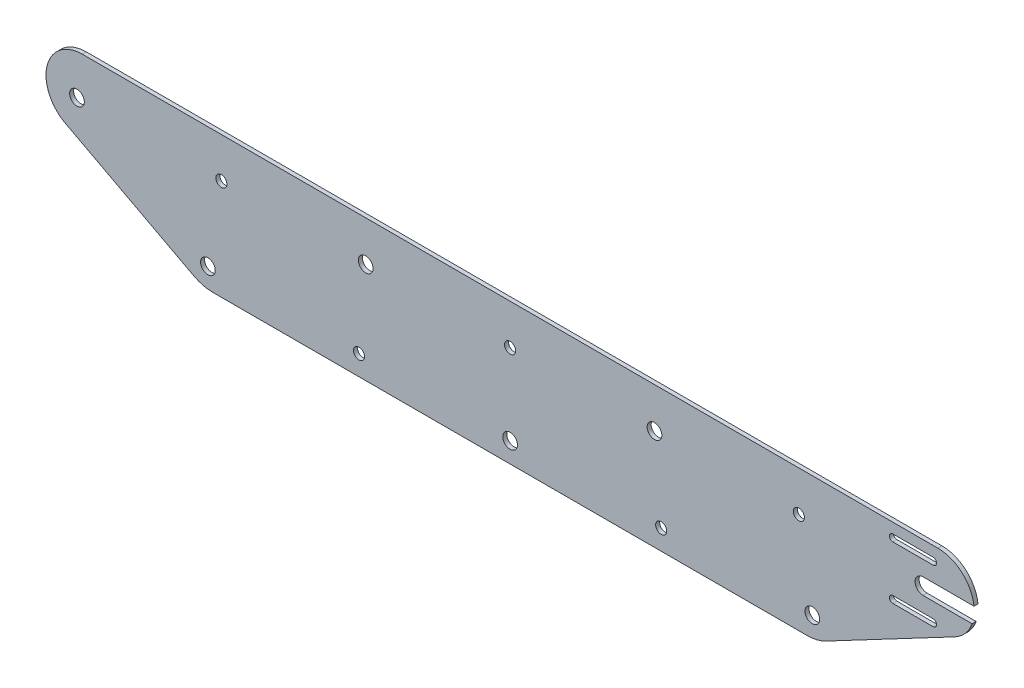
SolidWorks part; units mm, degrees
ref_plane "Plan de face" through (0, 0, 0) normal (0, 0, 1) x (1, 0, 0)
ref_plane "Plan de dessus" through (0, 0, 0) normal (0, 1, 0) x (1, 0, 0)
ref_plane "Plan de droite" through (0, 0, 0) normal (1, 0, 0) x (0, 0, -1)
sketch "Esquisse1" plane through (0, 0, 0) normal (0, 0, 1) x (1, 0, 0)
  line L0 (0, 0) -> (0, 122.747) construction
  line L1 (-215, -20) -> (215, -20) construction
  line L2 (-215, -20) -> (-215, 20) construction
  line L3 (-215, 20) -> (215, 20) construction
  line L4 (215, -20) -> (215, 20) construction
  line L5 (-215, -20) -> (215, 20) construction
  line L6 (-215, 20) -> (215, -20) construction
  line L7 (-1220, 0) -> (-150, 0) construction
  line L8 (-284.959, 40) -> (-150, 40)
  line L9 (150, 40) -> (284.959, 40)
  line L10 (150, 0) -> (150, -20) construction
  line L11 (150, -20) -> (-150, -20) construction
  line L12 (-150, 0) -> (-150, -20) construction
  line L13 (150, 0) -> (-150, -20) construction
  line L14 (150, -20) -> (-150, 0) construction
  line L15 (-284.959, 40) -> (-152.4795, -30)
  line L16 (-152.4795, -30) -> (152.4795, -30)
  line L17 (284.959, 40) -> (152.4795, -30)
  line L18 (-215, 20) -> (-71.6667, 20) construction
  line L19 (-71.6667, 20) -> (71.6667, 20) construction
  line L20 (71.6667, 20) -> (215, 20) construction
  line L21 (150, 0) -> (193.5165, 0) construction
  line L22 (150, 95) -> (-150, 95) construction
  line L23 (150, 95) -> (150, 40) construction
  line L24 (-150, 40) -> (150, 40)
  line L25 (-150, 95) -> (-150, 40) construction
  line L26 (150, 95) -> (-150, 0) construction
  line L27 (150, 0) -> (-150, 95) construction
  circle A0 centre (-215, 20) radius 3.65
  circle A1 centre (-150, -20) radius 3.65
  circle A2 centre (150, -20) radius 3.65
  circle A3 centre (215, 20) radius 3.65
  circle A4 centre (0, -20) radius 3.65
  circle A5 centre (-71.6667, 20) radius 3.65
  circle A6 centre (71.6667, 20) radius 3.65
  circle A7 centre (0, 78.03) radius 3.65 construction
  point P0 (0, 0)
  point P8 (0, -10)
  point P20 (0, 47.5)
  point P21 (0, -30)
  point P31 (0, 47.5)
  dimension "D8" = 7.3
  dimension "D10" = 58.03
  dimension "D1" = 430
  dimension "D2" = 40
  dimension "D3" = 300
  dimension "D4" = 20
  dimension "D5" = 15
  dimension "D6" = 10
  dimension "D7" = 10
  dimension "D9" = 55
extrude "Boss.-Extru.1" add sketch "Esquisse1" along normal blind 2
fillet "Congé1" radius 18 2 edges at (-284.959, 40, 1) (284.959, 40, 1)
fillet "Congé2" radius 20 2 edges at (-152.4795, -30, 1) (152.4795, -30, 1)
hole_wizard "Dégagement M31" positions "Esquisse3" profile "Esquisse2" hole size "M3" standard "Ansi Metric" end condition through all
sketch "Esquisse3" plane through (0, 0, 0) normal (0, 0, -1) x (-1, 0, 0)
  line L0 (-215, 12.5) -> (-215, 20)
  line L1 (-200, 6.7712) -> (-200, 33.2288)
  circle A0 centre (-215, 20) radius 7.5
  circle A1 centre (-215, 20) radius 20
  point P0 (-200, 33.2288)
  point P29 (-200, 6.7712)
  dimension "D2" = 15
  dimension "D3" = 40
  dimension "D1" = 15
sketch "Esquisse2" plane through (200, 33.2288, 0) normal (1, 0, 0) x (0, 1, 0)
  line L0 (0, 0) -> (0, 2)
  line L1 (0, 2) -> (1.7, 2)
  line L2 (1.7, 2) -> (1.7, 0)
  line L5 (1.7, 0) -> (0, 0)
  line L11 (0, -6.35) -> (0, 107.95) construction
  dimension "Diamètre du perçage jusqu'au prochain" = 3.4
  dimension "Profondeur du perçage jusqu'au prochain" = 2
sketch "Esquisse4" plane through (0, 0, 0) normal (0, 0, -1) x (-1, 0, 0)
  line L0 (-215, 24) -> (-230.2521, 24)
  line L1 (-215, 24) -> (-205, 24)
  line L2 (-215, 16) -> (-205, 16)
  line L3 (-215, 16) -> (-229.3341, 16)
  line L4 (-147.5205, -30) -> (147.5205, -30)
  line L5 (156.8641, -27.6833) -> (220.7728, 6.0851)
  line L6 (212.3636, 40) -> (-212.3636, 40)
  line L7 (-220.7728, 6.0851) -> (-156.8641, -27.6833)
  line L8 (-147.5205, -30) -> (147.5205, -30)
  line L9 (156.8641, -27.6833) -> (220.7728, 6.0851)
  line L10 (212.3636, 40) -> (-212.3636, 40)
  line L11 (-220.7728, 6.0851) -> (-156.8641, -27.6833)
  line L12 (-215, 16) -> (-215, 24)
  line L13 (-200, 34.9288) -> (-210, 34.9288)
  line L14 (-200, 34.9288) -> (-200, 31.5288)
  line L15 (-210, 31.5288) -> (-200, 31.5288)
  line L16 (-200, 31.5288) -> (-190, 31.5288)
  line L17 (-200, 8.4712) -> (-210, 8.4712)
  line L18 (-190, 34.9288) -> (-200, 34.9288)
  line L19 (-200, 8.4712) -> (-200, 5.0712)
  line L20 (-210, 5.0712) -> (-200, 5.0712)
  line L21 (-200, 5.0712) -> (-190, 5.0712)
  line L22 (-190, 8.4712) -> (-200, 8.4712)
  line L23 (-175, 14.2) -> (-185, 14.2)
  line L24 (-175, 14.2) -> (-175, 10.8)
  line L25 (-185, 10.8) -> (-175, 10.8)
  line L26 (-175, 10.8) -> (-165, 10.8)
  line L27 (-165, 14.2) -> (-175, 14.2)
  line L28 (-185, 14.2) -> (-228.5858, 14.2)
  line L29 (-185, 10.8) -> (-226.4547, 10.8)
  arc A2 (-205, 24) -> (-205, 16) centre (-205, 20) cw
  circle A3 centre (-215, 20) radius 3.65 construction
  arc A4 (147.5205, -30) -> (156.8641, -27.6833) centre (147.5205, -10) ccw
  arc A5 (220.7728, 6.0851) -> (212.3636, 40) centre (212.3636, 22) ccw
  arc A6 (-212.3636, 40) -> (-220.7728, 6.0851) centre (-212.3636, 22) ccw
  arc A7 (-156.8641, -27.6833) -> (-147.5205, -30) centre (-147.5205, -10) ccw
  arc A8 (147.5205, -30) -> (156.8641, -27.6833) centre (147.5205, -10) ccw
  arc A9 (220.7728, 6.0851) -> (212.3636, 40) centre (212.3636, 22) ccw
  arc A10 (-212.3636, 40) -> (-220.7728, 6.0851) centre (-212.3636, 22) ccw
  arc A11 (-156.8641, -27.6833) -> (-147.5205, -30) centre (-147.5205, -10) ccw
  circle A12 centre (-200, 33.2288) radius 1.7 construction
  circle A13 centre (-200, 33.2288) radius 1.7 construction
  arc A14 (-190, 34.9288) -> (-190, 31.5288) centre (-190, 33.2288) cw
  arc A15 (-210, 34.9288) -> (-210, 31.5288) centre (-210, 33.2288) ccw
  arc A16 (-190, 8.4712) -> (-190, 5.0712) centre (-190, 6.7712) cw
  arc A17 (-210, 8.4712) -> (-210, 5.0712) centre (-210, 6.7712) ccw
  arc A18 (-165, 14.2) -> (-165, 10.8) centre (-165, 12.5) cw
  circle A20 centre (-200, 6.7712) radius 1.7 construction
  point P17 (-215, 20)
  point P32 (-200, 33.2288)
  point P41 (-200, 6.7712)
  point P52 (-175, 12.5)
  dimension "D2" = 10
  dimension "D3" = 8
  dimension "D4" = 10
  dimension "D5" = 10
  dimension "D6" = 10
  dimension "D1" = 0
extrude "Enlèv. mat.-Extru.1" cut sketch "Esquisse4" against normal through all contours L3 A15 L0 A6 | A2 L1 A15 L2 | A14 L18 L2 L16 | L13 A15 L15 L2 | L17 A17 L20 L4 | A16 L22 L4 L21
hole_wizard "Dégagement M51" positions "Esquisse6" profile "Esquisse5" hole size "M5" standard "Ansi Metric" end condition through all
sketch "Esquisse6" plane through (0, 0, 0) normal (0, 0, -1) x (-1, 0, 0)
  line L0 (215, 20) -> (31.0935, 20) construction
  line L2 (215, 20) -> (143.3333, 20)
  line L4 (143.3333, 20) -> (71.6667, 20)
  line L5 (71.6667, 20) -> (0, 20)
  line L6 (0, 20) -> (-71.6667, 20)
  line L7 (-71.6667, 20) -> (-143.3333, 20)
  circle A2 centre (215, 20) radius 3.65
  circle A3 centre (215, 20) radius 3.65 construction
  circle A4 centre (-71.6667, 20) radius 3.65
  circle A5 centre (-71.6667, 20) radius 3.65 construction
  point P0 (143.3333, 20)
  point P2 (0, 20)
  point P37 (-143.3333, 20)
sketch "Esquisse5" plane through (-143.3333, 20, 0) normal (1, 0, 0) x (0, 1, 0)
  line L0 (0, 0) -> (0, 2)
  line L1 (0, 2) -> (2.75, 2)
  line L2 (2.75, 2) -> (2.75, 0)
  line L5 (2.75, 0) -> (0, 0)
  line L11 (0, -6.35) -> (0, 107.95) construction
  dimension "Diamètre du perçage jusqu'au prochain" = 5.5
  dimension "Profondeur du perçage jusqu'au prochain" = 2
hole_wizard "Dégagement M52" positions "Esquisse8" profile "Esquisse7" hole size "M5" standard "Ansi Metric" end condition through all
sketch "Esquisse8" plane through (0, 0, 2) normal (0, 0, 1) x (1, 0, 0)
  line L0 (-150, -20) -> (-75, -20)
  line L1 (-75, -20) -> (0, -20)
  line L2 (0, -20) -> (75, -20)
  line L3 (75, -20) -> (150, -20)
  point P0 (-75, -20)
  point P2 (75, -20)
sketch "Esquisse7" plane through (-75, -20, 2) normal (1, 0, 0) x (0, -1, 0)
  line L0 (0, 0) -> (0, 2)
  line L1 (0, 2) -> (2.75, 2)
  line L2 (2.75, 2) -> (2.75, 0)
  line L5 (2.75, 0) -> (0, 0)
  line L11 (0, -6.35) -> (0, 107.95) construction
  dimension "Diamètre du perçage jusqu'au prochain" = 5.5
  dimension "Profondeur du perçage jusqu'au prochain" = 2
